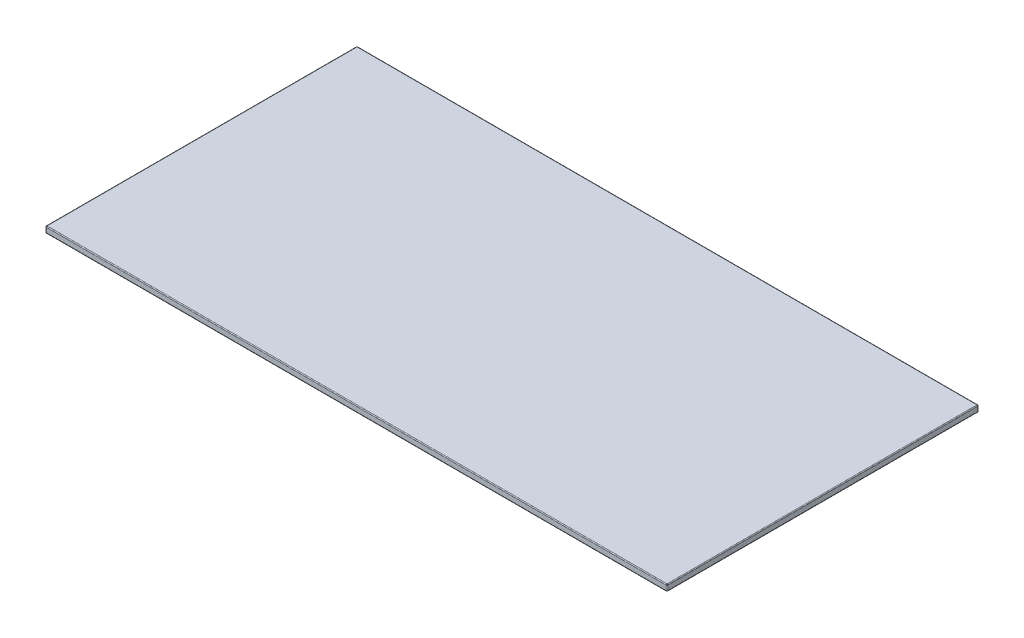
SolidWorks part; units mm, degrees
material "Maple"
ref_plane "Front Plane" through (0, 0, 0) normal (0, 0, 1) x (1, 0, 0)
ref_plane "Top Plane" through (0, 0, 0) normal (0, 1, 0) x (1, 0, 0)
ref_plane "Right Plane" through (0, 0, 0) normal (1, 0, 0) x (0, 0, -1)
sketch "Sketch1" plane through (0, 0, 0) normal (0, 1, 0) x (1, 0, 0)
  line L1 (1018.3812, -510.3812) -> (-1018.3813, -510.3813)
  line L2 (1018.3812, -510.3812) -> (1018.3812, 510.3813)
  line L3 (1018.3812, 510.3813) -> (-1018.3813, 510.3812)
  line L4 (-1018.3813, -510.3813) -> (-1018.3813, 510.3812)
  line L5 (1018.3812, -510.3812) -> (-1018.3813, 510.3812) construction
  line L6 (1018.3812, 510.3813) -> (-1018.3813, -510.3813) construction
  point P0 (0, 0)
  dimension "D1" = 2036.7625
  dimension "D2" = 1020.7625
extrude "Boss-Extrude1" add sketch "Sketch1" along normal blind 20.6375
fillet "Fillet2" radius 2.54 12 edges at (0, 0, 510.3813) (1018.3812, 0, 0) (0, 0, -510.3813) (-1018.3813, 0, 0) (0, 20.6375, -510.3813) (1018.3812, 20.6375, 0) (0, 20.6375, 510.3813) (-1018.3813, 20.6375, 0) (1018.3812, 10.3187, 510.3812) (1018.3812, 10.3187, -510.3813) (-1018.3813, 10.3187, 510.3813) (-1018.3813, 10.3187, -510.3812)
